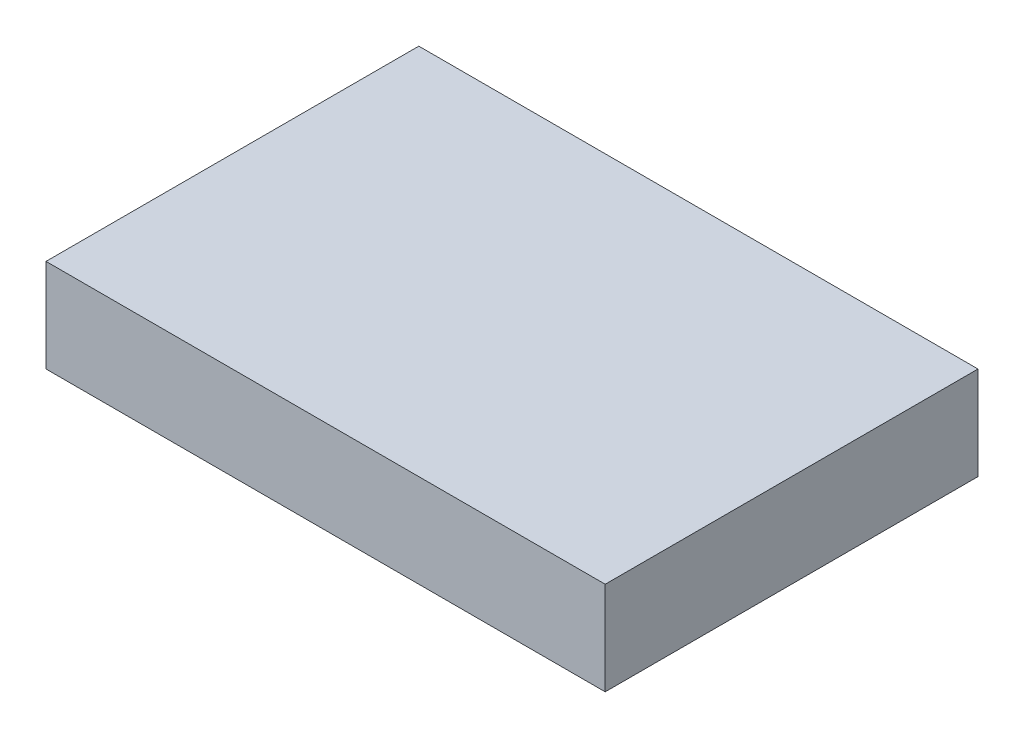
SolidWorks part; units mm, degrees
ref_plane "Front Plane" through (0, 0, 0) normal (0, 0, 1) x (1, 0, 0)
ref_plane "Top Plane" through (0, 0, 0) normal (0, 1, 0) x (1, 0, 0)
ref_plane "Right Plane" through (0, 0, 0) normal (1, 0, 0) x (0, 0, -1)
sketch "Sketch4" plane through (0, 0, 0) normal (0, 1, 0) x (1, 0, 0)
  line L1 (0, 0) -> (76.2, 0)
  line L2 (0, 0) -> (0, 50.8)
  line L3 (0, 50.8) -> (76.2, 50.8)
  line L4 (76.2, 0) -> (76.2, 50.8)
extrude "Extrude2" add sketch "Sketch4" against normal blind 12.7
sketch "Sketch5" plane through (0, 0, 0) normal (0, 1, 0) x (1, 0, 0)
  line L8 (3.175, 44.45) -> (3.175, 6.35)
  line L9 (6.35, 3.175) -> (69.85, 3.175)
  line L10 (73.025, 6.35) -> (73.025, 44.45)
  line L11 (69.85, 47.625) -> (6.35, 47.625)
  arc A0 (3.175, 44.45) -> (6.35, 47.625) centre (6.35, 44.45) cw
  arc A1 (3.175, 6.35) -> (6.35, 3.175) centre (6.35, 6.35) ccw
  arc A2 (69.85, 3.175) -> (73.025, 6.35) centre (69.85, 6.35) ccw
  arc A3 (73.025, 44.45) -> (69.85, 47.625) centre (69.85, 44.45) ccw
